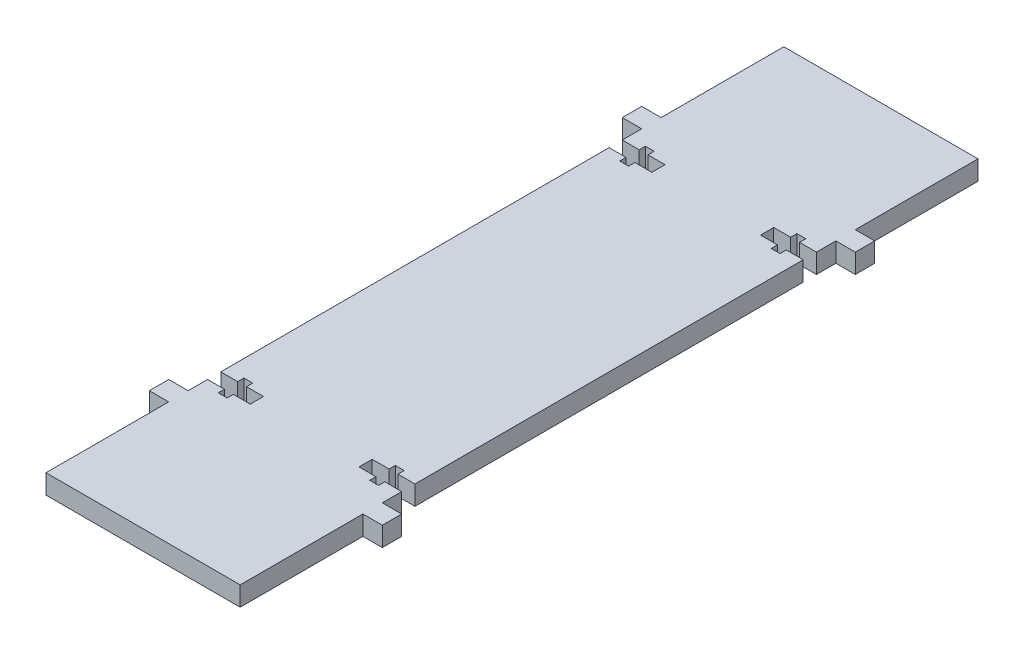
SolidWorks part; units mm, degrees
ref_plane "Front Plane" through (0, 0, 0) normal (0, 0, 1) x (1, 0, 0)
ref_plane "Top Plane" through (0, 0, 0) normal (0, 1, 0) x (1, 0, 0)
ref_plane "Right Plane" through (0, 0, 0) normal (1, 0, 0) x (0, 0, -1)
sketch "Elevator Belt Backplate" plane through (0, 0, 0) normal (0, 1, 0) x (1, 0, 0)
  line L0 (-31.75, 0) -> (31.75, 0) construction
  line L1 (-31.75, -120.65) -> (31.75, -120.65)
  line L2 (-31.75, -120.65) -> (-31.75, -80.518)
  line L3 (-31.75, 120.65) -> (31.75, 120.65)
  line L4 (31.75, -120.65) -> (31.75, -80.518)
  line L5 (-31.75, -120.65) -> (31.75, 120.65) construction
  line L6 (-31.75, 120.65) -> (31.75, -120.65) construction
  line L7 (31.75, 80.518) -> (31.75, 120.65)
  line L8 (31.75, 74.168) -> (38.1, 74.168)
  line L9 (0, 120.65) -> (0, -120.65) construction
  line L10 (31.75, 80.518) -> (38.1, 80.518)
  line L11 (38.1, 74.168) -> (38.1, 80.518)
  line L12 (31.75, -80.518) -> (38.1, -80.518)
  line L13 (38.1, -74.168) -> (38.1, -80.518)
  line L14 (31.75, -74.168) -> (38.1, -74.168)
  line L15 (-31.75, 80.518) -> (-38.1, 80.518)
  line L16 (-31.75, -74.168) -> (-38.1, -74.168)
  line L17 (-38.1, -74.168) -> (-38.1, -80.518)
  line L18 (-31.75, -80.518) -> (-38.1, -80.518)
  line L19 (-38.1, 74.168) -> (-38.1, 80.518)
  line L20 (-31.75, 74.168) -> (-38.1, 74.168)
  line L21 (-31.75, 80.518) -> (-31.75, 120.65)
  line L22 (-31.75, -74.168) -> (-31.75, -67.818)
  line L23 (31.75, -74.168) -> (31.75, -67.818)
  line L24 (-31.75, 67.818) -> (-26.215, 67.818)
  line L25 (-26.215, 67.818) -> (-26.215, 69.859)
  line L26 (-26.215, 69.859) -> (-23.315, 69.859)
  line L27 (-23.315, 69.859) -> (-23.315, 67.818)
  line L28 (-23.315, 67.818) -> (-17.78, 67.818)
  line L29 (-17.78, 67.818) -> (-17.78, 63.5)
  line L30 (-17.78, 63.5) -> (-23.315, 63.5)
  line L31 (-23.315, 63.5) -> (-23.315, 61.459)
  line L32 (-23.315, 61.459) -> (-26.215, 61.459)
  line L33 (-26.215, 61.459) -> (-26.215, 63.5)
  line L34 (-26.215, 63.5) -> (-31.75, 63.5)
  line L35 (-31.75, 67.818) -> (-31.75, 74.168)
  line L36 (31.75, 67.818) -> (26.215, 67.818)
  line L37 (23.315, 69.859) -> (23.315, 67.818)
  line L38 (26.215, 67.818) -> (26.215, 69.859)
  line L39 (26.215, 69.859) -> (23.315, 69.859)
  line L40 (23.315, 67.818) -> (17.78, 67.818)
  line L41 (26.215, 63.5) -> (31.75, 63.5)
  line L42 (26.215, 61.459) -> (26.215, 63.5)
  line L43 (23.315, 61.459) -> (26.215, 61.459)
  line L44 (23.315, 63.5) -> (23.315, 61.459)
  line L45 (17.78, 63.5) -> (23.315, 63.5)
  line L46 (17.78, 67.818) -> (17.78, 63.5)
  line L47 (31.75, 67.818) -> (31.75, 74.168)
  line L48 (26.215, -63.5) -> (31.75, -63.5)
  line L49 (31.75, -67.818) -> (26.215, -67.818)
  line L50 (17.78, -63.5) -> (23.315, -63.5)
  line L51 (17.78, -67.818) -> (17.78, -63.5)
  line L52 (23.315, -67.818) -> (17.78, -67.818)
  line L53 (23.315, -63.5) -> (23.315, -61.459)
  line L54 (23.315, -61.459) -> (26.215, -61.459)
  line L55 (26.215, -61.459) -> (26.215, -63.5)
  line L56 (26.215, -69.859) -> (23.315, -69.859)
  line L57 (26.215, -67.818) -> (26.215, -69.859)
  line L58 (23.315, -69.859) -> (23.315, -67.818)
  line L59 (-17.78, -67.818) -> (-17.78, -63.5)
  line L60 (-26.215, -63.5) -> (-31.75, -63.5)
  line L61 (-26.215, -61.459) -> (-26.215, -63.5)
  line L62 (-23.315, -61.459) -> (-26.215, -61.459)
  line L63 (-23.315, -63.5) -> (-23.315, -61.459)
  line L64 (-17.78, -63.5) -> (-23.315, -63.5)
  line L65 (-23.315, -67.818) -> (-17.78, -67.818)
  line L66 (-23.315, -69.859) -> (-23.315, -67.818)
  line L67 (-26.215, -69.859) -> (-23.315, -69.859)
  line L68 (-26.215, -67.818) -> (-26.215, -69.859)
  line L69 (-31.75, -67.818) -> (-26.215, -67.818)
  line L70 (31.75, -63.5) -> (31.75, 63.5)
  line L71 (-31.75, -63.5) -> (-31.75, 63.5)
  point P0 (0, 0)
  point P26 (-94.3248, 77.7538)
  dimension "D1" = 6.35
  dimension "D2" = 6.35
  dimension "D3" = 6.35
  dimension "D4" = 63.5
  dimension "D5" = 241.3
  dimension "D6" = 4.318
  dimension "D7" = 2.9
  dimension "D8" = 8.4
  dimension "D9" = 13.97
  dimension "D10" = 63.5
extrude "Boss-Extrude1" add sketch "Elevator Belt Backplate" along normal blind 6.35
equation "\"Ball Diameter\"= 1.75in"
equation "\"Sheet Thickness\"= 0.25in"
equation "\"Screw Diameter\"= .17in"
equation "\"Robot Diameter\"= 14in"
equation "\"Castor Screw Diameter\"= 0.22in"
equation "\"Wheel Diameter\" = 4in"
equation "\"Nut Diameter\" = 8.4mm"
equation "\"Nut Height\" = 2.9mm"
equation "\"Screw Height\" = 0.55in"
equation "\"Pulley Diameter\" = 1in"
equation "\"Reactor Height\" = 14in"
equation "\"Elevator Height\" = 11.5in"
equation "\"Elevator Width\" = \"Ball Diameter\" + 0.25in"
equation "\"Elevator Bearing Diameter\" = sqr(2*(\"Sheet Thickness\"^2)) + 0.2in"
equation "\"Elevator Axle Length\" = \"Elevator Width\" + 6*\"Sheet Thickness\""
equation "\"D7@Elevator Belt Backplate\"=\"Sheet Thickness\""
equation "\"D8@Elevator Belt Backplate\"=\"Sheet Thickness\""
equation "\"D4@Elevator Belt Backplate\"=\"Elevator Width\" + 2 * \"Sheet Thickness\""
equation "\"D5@Elevator Belt Backplate\"=\"Elevator Height\"-\"Pulley Diameter\"-1in"
equation "\"D1@Boss-Extrude1\"=\"Sheet Thickness\""
equation "\"D6@Elevator Belt Backplate\" = \"Screw Diameter\""
equation "\"D7@Elevator Belt Backplate\"=\"Nut Height\""
equation "\"D8@Elevator Belt Backplate\"=\"Nut Diameter\""
equation "\"D9@Elevator Belt Backplate\"=\"Screw Height\""
